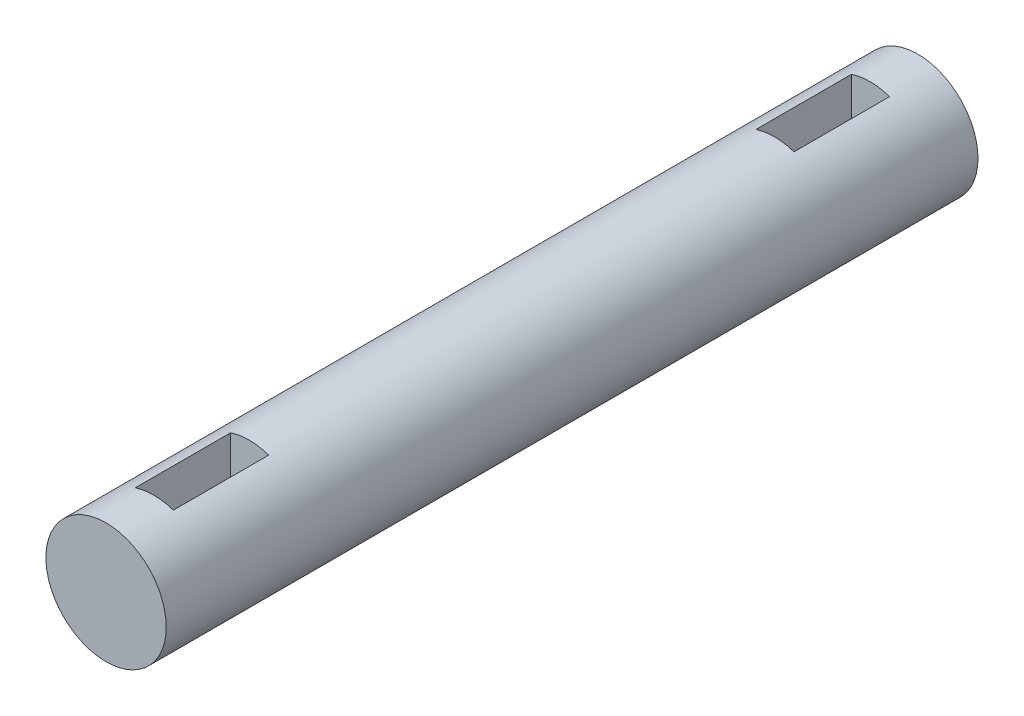
SolidWorks part; units mm, degrees
material "Alloy Steel"
ref_plane "Front Plane" through (0, 0, 0) normal (0, 0, 1) x (1, 0, 0)
ref_plane "Top Plane" through (0, 0, 0) normal (0, 1, 0) x (1, 0, 0)
ref_plane "Right Plane" through (0, 0, 0) normal (1, 0, 0) x (0, 0, -1)
sketch "Sketch1" plane through (0, 0, 0) normal (0, 0, 1) x (1, 0, 0)
  circle A0 centre (0, 0) radius 6.3
extrude "Boss-Extrude1" add sketch "Sketch1" along normal blind 80 and the other way blind 5
sketch "Sketch6" plane through (0, 0, 0) normal (0, 1, 0) x (1, 0, 0)
  line L0 (0, 0) -> (0, -70)
  line L1 (0, -70) -> (-1.9552, -70)
  line L2 (-1.9552, -70) -> (-1.9552, -65.0081)
  line L3 (-1.9552, -65.0081) -> (0, -65.0081)
  line L4 (0, -65.0081) -> (2.0384, -65.0081)
  line L5 (2.0384, -65.0081) -> (2.0384, -74.9919)
  line L6 (2.0384, -74.9919) -> (-1.9552, -74.9919)
  line L7 (-1.9552, -74.9919) -> (-1.9552, -70)
  line L8 (0, 0) -> (-1.9552, 0)
  line L11 (2.0384, -10) -> (-1.9552, -10)
  line L14 (-1.9552, 0) -> (-1.9552, -10)
  line L15 (0, 0) -> (2.0384, 0)
  line L16 (2.0384, 0) -> (2.0384, -10)
  dimension "D1" = 1.9552
  dimension "D2" = 4.9919
  dimension "D3" = 9.9838
  dimension "D4" = 3.9935
  dimension "D5" = 70
  dimension "D6" = 10
  dimension "D7" = 3.9935
extrude "Cut-Extrude1" cut sketch "Sketch6" along normal blind 10 contours L2 L3 L4 L5 L6 L7 | L15 L16 L11 L14 L8
